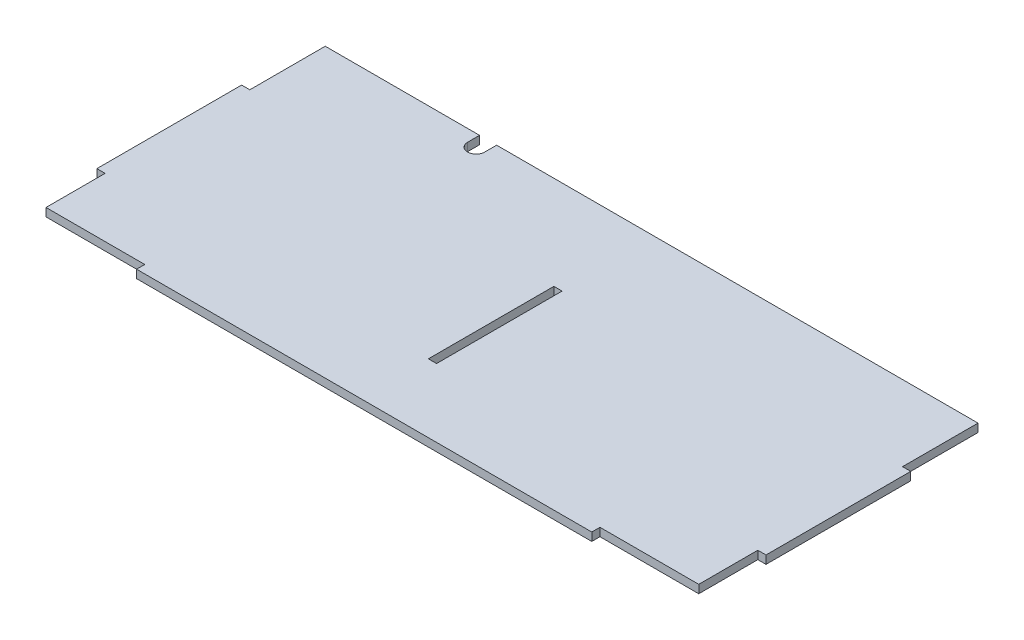
SolidWorks part; units mm, degrees
ref_plane "Front Plane" through (0, 0, 0) normal (0, 0, 1) x (1, 0, 0)
ref_plane "Top Plane" through (0, 0, 0) normal (0, 1, 0) x (1, 0, 0)
ref_plane "Right Plane" through (0, 0, 0) normal (1, 0, 0) x (0, 0, -1)
sketch "Sketch1" plane through (0, 0, 0) normal (0, 1, 0) x (1, 0, 0)
  line L1 (0, 0) -> (490, 0)
  line L2 (0, 0) -> (0, 210.49)
  line L3 (0, 210.49) -> (490, 210.49)
  line L4 (490, 0) -> (490, 210.49)
  dimension "D1" = 490
  dimension "D2" = 210.49
extrude "Boss-Extrude1" add sketch "Sketch1" along normal blind 6
sketch "Sketch2" plane through (0, 6, 0) normal (0, 1, 0) x (1, 0, 0)
  line L0 (411.6667, 6) -> (411.6667, 0)
  line L1 (490, 0) -> (411.6667, 0)
  line L2 (411.6667, 6) -> (484, 6)
  line L3 (0, 49.25) -> (0, 0)
  line L5 (490, 210.49) -> (484, 210.49)
  line L6 (490, 210.49) -> (490, 155.24)
  line L7 (490, 155.24) -> (484, 155.24)
  line L8 (484, 210.49) -> (484, 155.24)
  line L9 (0, 210.49) -> (6, 210.49)
  line L10 (0, 210.49) -> (0, 155.24)
  line L11 (0, 155.24) -> (6, 155.24)
  line L12 (6, 210.49) -> (6, 155.24)
  line L13 (78.3333, 6) -> (78.3333, 0)
  line L18 (484, 6) -> (484, 49.25)
  line L19 (484, 49.25) -> (490, 49.25)
  line L20 (490, 0) -> (490, 210.49) construction
  line L21 (490, 49.25) -> (490, 0)
  line L22 (0, 210.49) -> (0, 0) construction
  line L23 (0, 49.25) -> (6, 49.25)
  line L24 (6, 49.25) -> (6, 6)
  line L25 (6, 6) -> (78.3333, 6)
  line L26 (78.3333, 0) -> (0, 0)
  dimension "D2" = 55.25
  dimension "D3" = 55.25
  dimension "D4" = 6
  dimension "D5" = 333.3333
  dimension "D6" = 6
  dimension "D7" = 6
  dimension "D8" = 78.3333
  dimension "D9" = 78.3333
  dimension "D10" = 6
  dimension "D11" = 6
  dimension "D12" = 49.25
  dimension "D13" = 6
  dimension "D14" = 49.25
extrude "Cut-Extrude1" cut sketch "Sketch2" against normal through all
sketch "Sketch3" plane through (0, 6, 0) normal (0, 1, 0) x (1, 0, 0)
  line L0 (78.3333, 0) -> (411.6667, 0) construction
  line L1 (242, 141.92) -> (248, 141.92)
  line L2 (242, 141.92) -> (242, 50)
  line L3 (242, 50) -> (248, 50)
  line L4 (248, 141.92) -> (248, 50)
  line L5 (0, 155.24) -> (0, 49.25) construction
  dimension "D1" = 6
  dimension "D2" = 91.92
  dimension "D3" = 50
  dimension "D4" = 242
extrude "Cut-Extrude2" cut sketch "Sketch3" against normal through all
sketch "Sketch4" plane through (0, 6, 0) normal (0, 1, 0) x (1, 0, 0)
  line L0 (119, 210.49) -> (119, 201.74)
  line L1 (484, 210.49) -> (6, 210.49) construction
  line L2 (131.5, 201.74) -> (131.5, 210.49)
  line L3 (131.5, 210.49) -> (119, 210.49)
  line L4 (0, 155.24) -> (0, 49.25) construction
  arc A2 (119, 201.74) -> (131.5, 201.74) centre (125.25, 201.74) ccw
  point P8 (125.25, 210.49)
  point P10 (125.25, 195.49)
  dimension "D1" = 12.5
  dimension "D2" = 119
  dimension "D3" = 15
extrude "Cut-Extrude3" cut sketch "Sketch4" against normal through all
